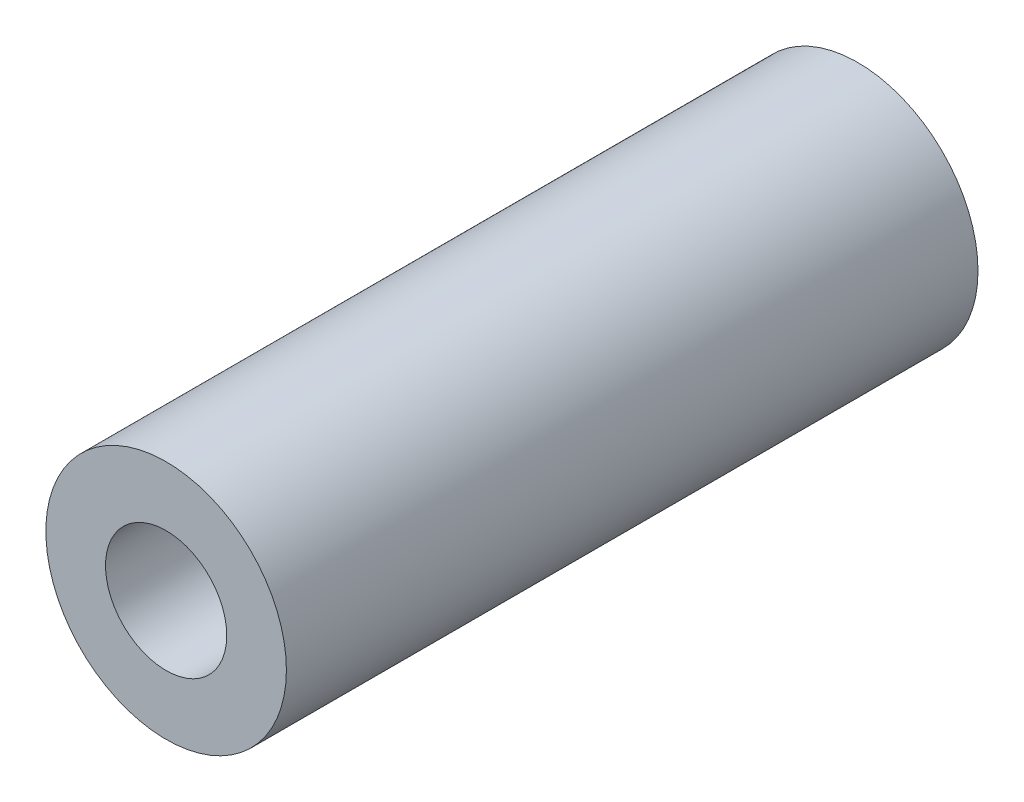
SolidWorks part; units mm, degrees
ref_plane "Front Plane" through (0, 0, 0) normal (0, 0, 1) x (1, 0, 0)
ref_plane "Top Plane" through (0, 0, 0) normal (0, 1, 0) x (1, 0, 0)
ref_plane "Right Plane" through (0, 0, 0) normal (1, 0, 0) x (0, 0, -1)
sketch "Sketch1" plane through (0, 0, 0) normal (0, 0, 1) x (1, 0, 0)
  line L0 (0, 3.2004) -> (0, 6.35) construction
  line L1 (0, -3.2004) -> (0, -6.35) construction
  circle A0 centre (0, 0) radius 6.35
  circle A1 centre (0, 0) radius 3.2004
  dimension "OD" = 12.7
  dimension "ID" = 6.4008
sketch "Sketch2" plane through (0, 0, 0) normal (1, 0, 0) x (0, 0, -1)
  line L0 (-18.2562, 3.2004) -> (18.2562, 3.2004) construction
  line L1 (-18.2562, -3.2004) -> (18.2562, -3.2004) construction
  line L2 (-18.2562, -6.35) -> (18.2562, -6.35) construction
  line L3 (-18.2562, 6.35) -> (18.2562, 6.35) construction
  dimension "Length" = 36.5125
extrude "Extrude1" add sketch "Sketch1" along normal up to vertex (18.2563 mm away) and the other way up to vertex (18.2563 mm away) up to point (0, 3.2004, 18.2562) other way up to point (0, 3.2004, -18.2562)
sketch "Sketch3" plane through (0, 0, 18.2562) normal (0, 0, 1) x (1, 0, 0)
  circle A0 centre (0, 0) radius 3.2004 construction
  circle A3 centre (0, 0) radius 3.2004
  point P3 (-3.2004, 0)
